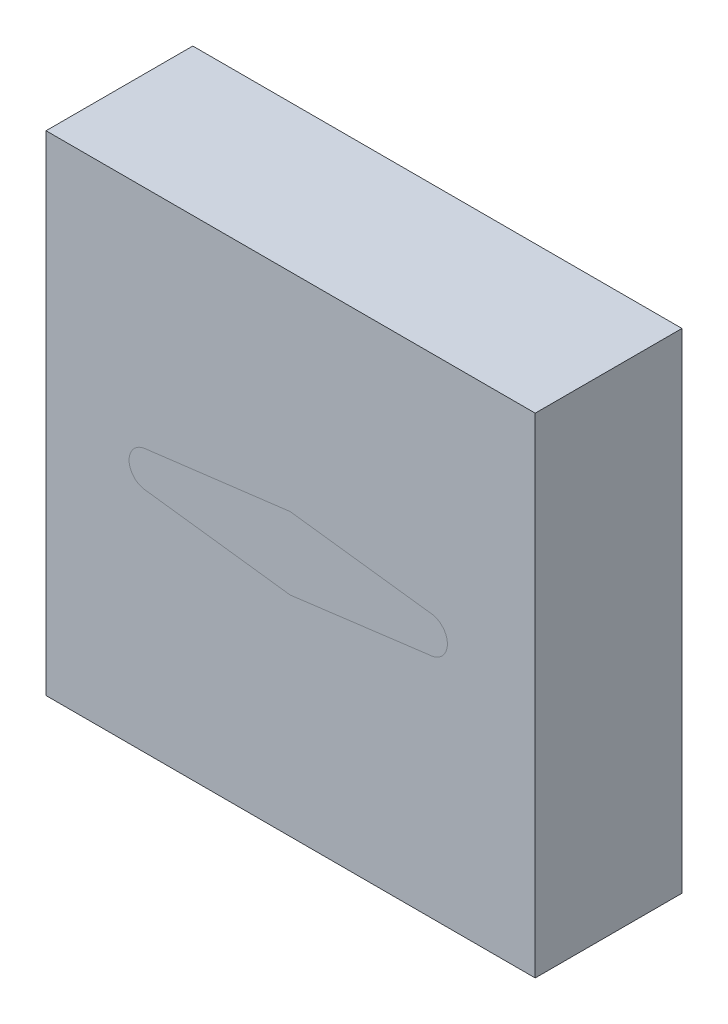
SolidWorks part; units mm, degrees
ref_plane "前视基准面" through (0, 0, 0) normal (0, 0, 1) x (1, 0, 0)
ref_plane "上视基准面" through (0, 0, 0) normal (0, 1, 0) x (1, 0, 0)
ref_plane "右视基准面" through (0, 0, 0) normal (1, 0, 0) x (0, 0, -1)
other "Configuration Table"
sketch "草图1" plane through (0, 0, 0) normal (0, 0, 1) x (1, 0, 0)
  line L1 (-25, 25) -> (25, 25)
  line L2 (-25, 25) -> (-25, -25)
  line L3 (-25, -25) -> (25, -25)
  line L4 (25, 25) -> (25, -25)
  line L5 (-25, 25) -> (25, -25) construction
  line L6 (-25, -25) -> (25, 25) construction
  point P0 (0, 0)
  dimension "D1" = 50
  dimension "D2" = 50
extrude "凸台-拉伸1" add sketch "草图1" along normal blind 15
sketch "草图2" plane through (0, 0, 15) normal (0, 0, 1) x (1, 0, 0)
  line L0 (-14.786, -1.745) -> (-0.0478, -3.6222)
  line L1 (-0.0478, -3.6222) -> (14.164, -1.8114)
  line L2 (-14.8212, 1.9266) -> (-0.0478, 3.7655)
  line L3 (-0.0478, 3.7655) -> (14.1405, 1.9704)
  line L4 (-0.0478, 3.7655) -> (-0.0478, -3.6222) construction
  line L5 (-14.6719, 0.0921) -> (14.136, 0.0794) construction
  arc A0 (-14.8212, 1.9266) -> (-14.786, -1.745) centre (-14.6719, 0.0921) ccw
  arc A1 (14.164, -1.8114) -> (14.1405, 1.9704) centre (14.136, 0.0794) ccw
  point P8 (-0.0478, 0.0717)
  point P9 (0, 0)
extrude "切除-拉伸1" cut sketch "草图2" against normal up to next
sketch "草图3" plane through (0, 0, 15) normal (0, 0, 1) x (1, 0, 0)
  line L0 (14.1405, 1.9704) -> (-0.0478, 3.7655) construction
  line L1 (-0.0478, -3.6222) -> (14.164, -1.8114) construction
  line L2 (-14.786, -1.745) -> (-0.0478, -3.6222) construction
  line L3 (-0.0478, 3.7655) -> (-14.8212, 1.9266) construction
  line L12 (14.1405, 1.9704) -> (-0.0478, 3.7655)
  line L13 (-0.0478, -3.6222) -> (14.164, -1.8114)
  line L14 (-14.786, -1.745) -> (-0.0478, -3.6222)
  line L15 (-0.0478, 3.7655) -> (-14.8212, 1.9266)
  arc A0 (14.164, -1.8114) -> (14.1405, 1.9704) centre (14.136, 0.0794) ccw construction
  arc A1 (-14.8212, 1.9266) -> (-14.786, -1.745) centre (-14.6719, 0.0921) ccw construction
  arc A2 (14.164, -1.8114) -> (14.1405, 1.9704) centre (14.136, 0.0794) ccw
  arc A3 (-14.8212, 1.9266) -> (-14.786, -1.745) centre (-14.6719, 0.0921) ccw
extrude "凸台-拉伸3" add sketch "草图3" against normal blind 10 separate body
